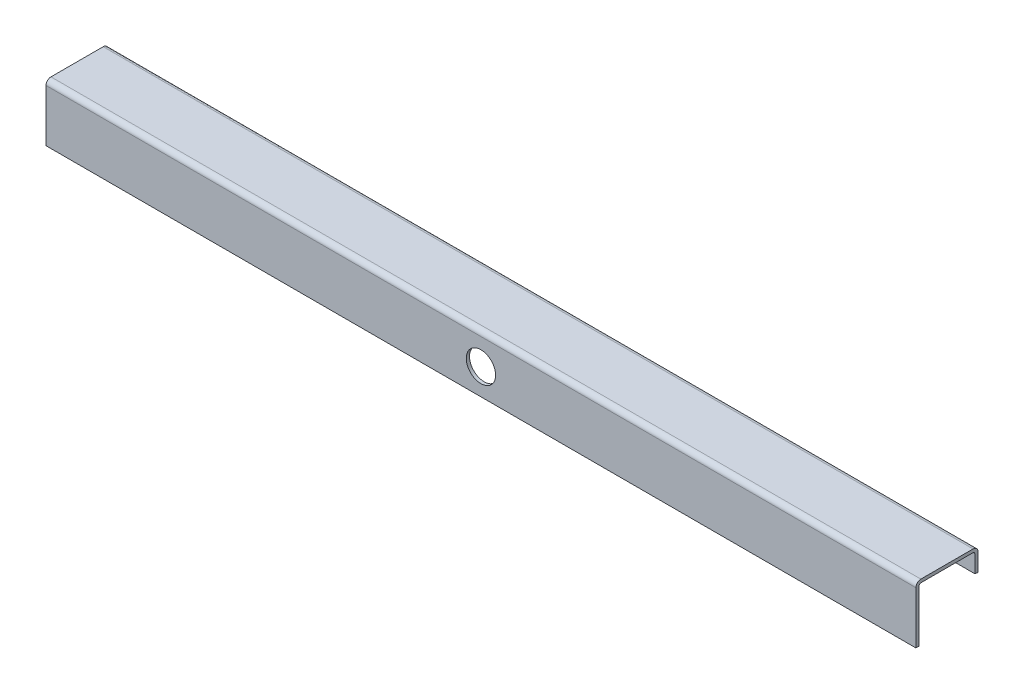
SolidWorks part; units mm, degrees
material "Plain Carbon Steel"
ref_plane "Front Plane" through (0, 0, 0) normal (0, 0, 1) x (1, 0, 0)
ref_plane "Top Plane" through (0, 0, 0) normal (0, 1, 0) x (1, 0, 0)
ref_plane "Right Plane" through (0, 0, 0) normal (1, 0, 0) x (0, 0, -1)
sketch "Sketch1" plane through (0, 0, 0) normal (1, 0, 0) x (0, 0, -1)
  line L0 (0, 19.9844) -> (0, 29.21)
  line L1 (-2.54, 31.75) -> (-29.21, 31.75)
  line L2 (-31.75, 29.21) -> (-31.75, 2.54)
  line L4 (-1.651, 20.3354) -> (-1.651, 29.21)
  line L5 (-2.54, 30.099) -> (-29.21, 30.099)
  line L6 (-30.099, 29.21) -> (-30.099, 2.54)
  line L8 (-1.651, 20.3354) -> (0, 19.9844)
  line L9 (-31.75, 2.54) -> (-30.099, 2.54)
  line L11 (-1.651, 2.54) -> (-1.651, 29.21) construction
  line L12 (0, 2.54) -> (0, 29.21) construction
  line L13 (-29.21, 1.651) -> (-2.54, 1.651) construction
  line L14 (-29.21, 0) -> (-2.54, 0) construction
  arc A2 (0, 29.21) -> (-2.54, 31.75) centre (-2.54, 29.21) ccw
  arc A3 (-31.75, 29.21) -> (-29.21, 31.75) centre (-29.21, 29.21) cw
  arc A4 (-1.651, 29.21) -> (-2.54, 30.099) centre (-2.54, 29.21) ccw
  arc A5 (-30.099, 29.21) -> (-29.21, 30.099) centre (-29.21, 29.21) cw
  arc A8 (-31.75, 2.54) -> (-29.21, 0) centre (-29.21, 2.54) ccw construction
  arc A9 (-30.099, 2.54) -> (-29.21, 1.651) centre (-29.21, 2.54) ccw construction
  arc A10 (0, 2.54) -> (-2.54, 0) centre (-2.54, 2.54) cw construction
  arc A11 (-1.651, 2.54) -> (-2.54, 1.651) centre (-2.54, 2.54) cw construction
  point P12 (0, 0)
  point P15 (0, 31.75)
  point P18 (-31.75, 31.75)
  dimension "D3" = 2.54
  dimension "D5" = 19.9844
  dimension "D1" = 31.75
  dimension "D2" = 31.75
  dimension "D6" = 20.3354
  dimension "D4" = 1.651
extrude "Boss-Extrude1" add sketch "Sketch1" along normal blind 177.8
scale "Scale1" scale about centroid uniform scaling no x scale factor 1 y scale factor 0.4 z scale factor 0.4
sketch "Sketch2" plane through (0, 0, 24.572) normal (0, 0, 1) x (1, 0, 0)
  line L0 (88.9, 15.4919) -> (88.9, 26.1599)
  line L1 (177.8, 15.4919) -> (0, 15.4919) construction
  line L2 (177.8, 26.1599) -> (0, 26.1599) construction
  circle A0 centre (88.9, 20.8259) radius 3
  point P6 (88.9, 20.8259)
  dimension "D1" = 6
extrude "Cut-Extrude1" cut sketch "Sketch2" against normal through all contours A0
